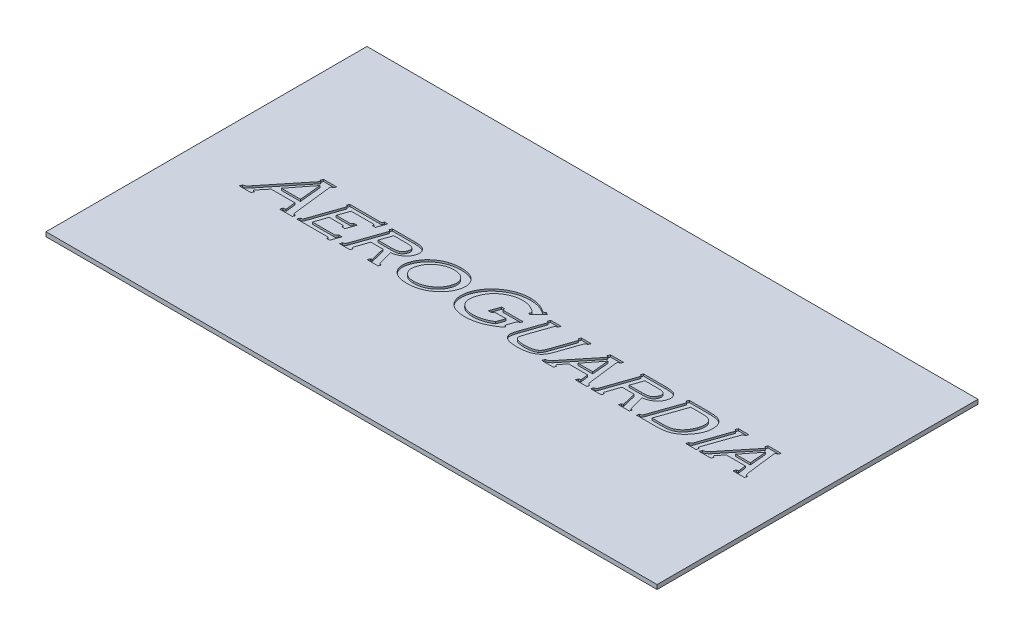
SolidWorks part; units mm, degrees
ref_plane "Alzado" through (0, 0, 0) normal (0, 0, 1) x (1, 0, 0)
ref_plane "Planta" through (0, 0, 0) normal (0, 1, 0) x (1, 0, 0)
ref_plane "Vista lateral" through (0, 0, 0) normal (1, 0, 0) x (0, 0, -1)
sketch "Croquis1" plane through (0, 0, 0) normal (0, 1, 0) x (1, 0, 0)
  line L1 (63.5, -33.35) -> (-63.5, -33.35)
  line L2 (63.5, -33.35) -> (63.5, 33.35)
  line L3 (63.5, 33.35) -> (-63.5, 33.35)
  line L4 (-63.5, -33.35) -> (-63.5, 33.35)
  line L5 (63.5, -33.35) -> (-63.5, 33.35) construction
  line L6 (63.5, 33.35) -> (-63.5, -33.35) construction
  point P0 (0, 0)
  dimension "D1" = 127
  dimension "D2" = 66.7
extrude "Saliente-Extruir1" add sketch "Croquis1" along normal blind 0.9
sketch "Croquis3" plane through (0, 0.9, 0) normal (0, 1, 0) x (1, 0, 0)
  line L0 (-60, -5) -> (60, -5) construction
  text T0 "<b><i>AeroGuardia</i></b>" font "Copperplate Gothic Light" height in points 48
  point P4 (0, 0)
  point P5 (0, 0)
  dimension "D1" = 120
  dimension "D2" = 5
  dimension "D3" = 60
extrude "Cortar-Extruir1" cut sketch "Croquis3" against normal blind 0.4
